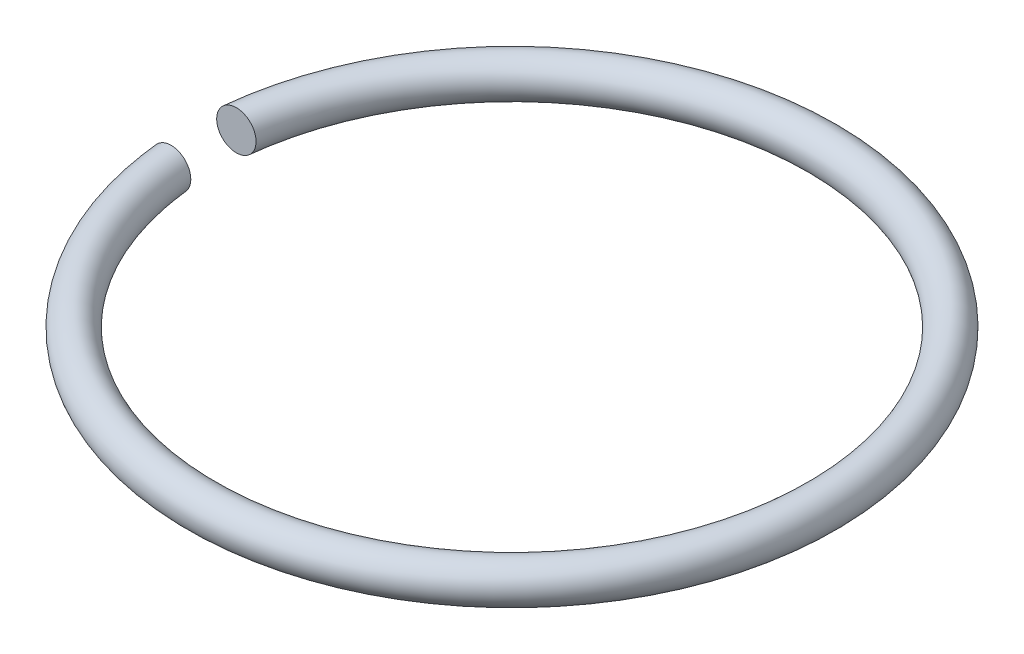
SolidWorks part; units mm, degrees
material "1.5805 (10NiCr5-4)"
ref_plane "Спереди" through (0, 0, 0) normal (0, 0, 1) x (1, 0, 0)
ref_plane "Сверху" through (0, 0, 0) normal (0, 1, 0) x (1, 0, 0)
ref_plane "Справа" through (0, 0, 0) normal (1, 0, 0) x (0, 0, -1)
sketch "Эскиз1" plane through (0, 0, 0) normal (0, 0, 1) x (1, 0, 0)
  line L0 (0, 0) -> (0, 5.376) construction
  circle A0 centre (-9.5, 0.6) radius 0.6
  dimension "D1" = 1.2
  dimension "D2" = 9.5
  dimension "D3" = 0.6
revolve "Повернуть1" add sketch "Эскиз1" angle 360 about L0
sketch "Эскиз2" plane through (0, 0, 0) normal (0, 1, 0) x (1, 0, 0)
  line L0 (0, 0) -> (-16.7656, 0) construction
  line L1 (-12.162, 1) -> (-7.1672, 1)
  line L2 (-12.162, 1) -> (-12.162, -1)
  line L3 (-12.162, -1) -> (-7.1672, -1)
  line L4 (-7.1672, 1) -> (-7.1672, -1)
  dimension "D1" = 1
  dimension "D2" = 1
extrude "Вырез-Вытянуть1" cut sketch "Эскиз2" against normal through all and the other way through all
ref_plane "Плоскость1" through (0, 0, 0) normal (0, -1, 0) x (-1, 0, 0)
